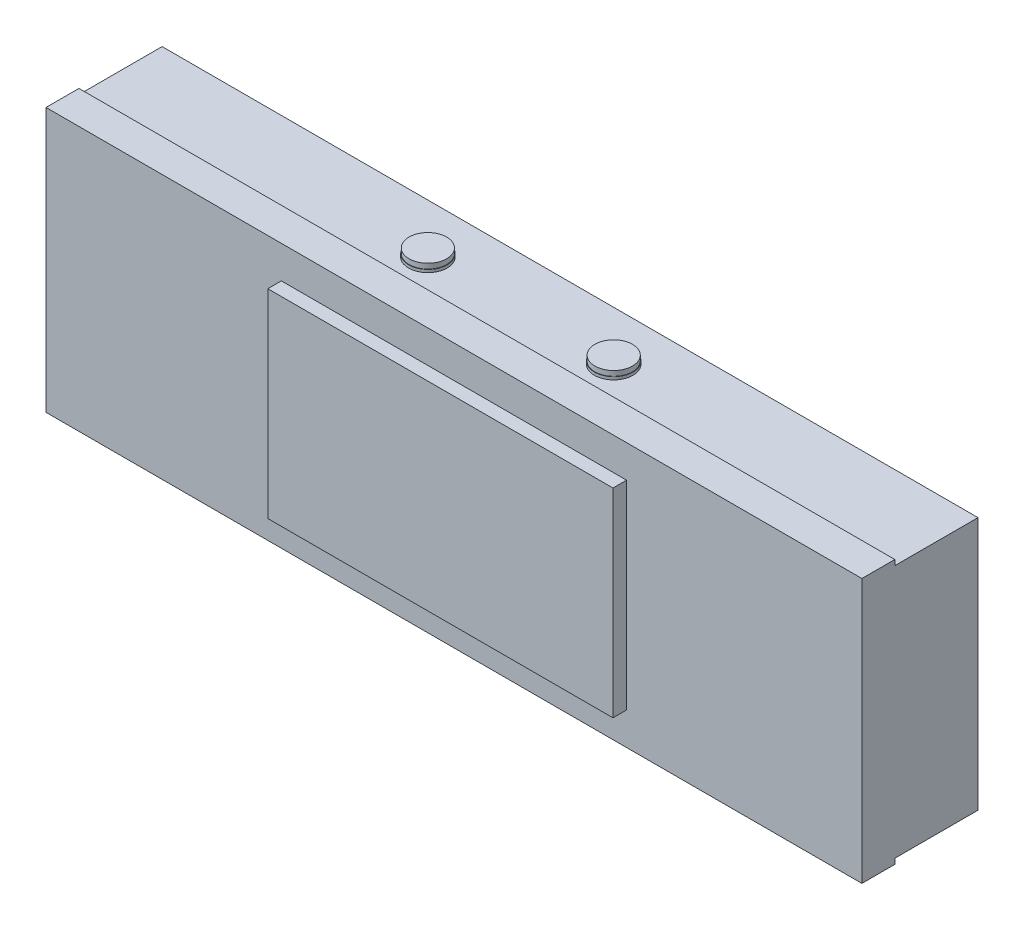
SolidWorks part; units mm, degrees
ref_plane "Front Plane" through (0, 0, 0) normal (0, 0, 1) x (1, 0, 0)
ref_plane "Top Plane" through (0, 0, 0) normal (0, 1, 0) x (1, 0, 0)
ref_plane "Right Plane" through (0, 0, 0) normal (1, 0, 0) x (0, 0, -1)
sketch "Sketch2" plane through (0, 0, 0) normal (1, 0, 0) x (0, 0, -1)
  line L0 (37, -40.375) -> (37, 40.375)
  line L1 (37, 40.375) -> (10.5, 40.375)
  line L2 (10.5, 40.375) -> (10.5, -40.375)
  line L3 (10.5, -40.375) -> (37, -40.375)
sketch "lid sketch" plane through (0, 0, 0) normal (1, 0, 0) x (0, 0, -1)
  line L0 (10.5, -42.075) -> (10.5, 42.075)
  line L1 (10.5, 42.075) -> (0, 42.075)
  line L2 (0, 42.075) -> (0, -42.075)
  line L3 (0, -42.075) -> (10.5, -42.075)
extrude "lid" add sketch "lid sketch" along normal mid plane 260
sketch "channel wall sketch" plane through (0, 0, 0) normal (1, 0, 0) x (0, 0, -1)
  line L0 (37, -40.375) -> (37, 40.375)
  line L1 (37, 40.375) -> (10.5, 40.375)
  line L2 (10.5, 40.375) -> (10.5, -40.375)
  line L3 (10.5, -40.375) -> (37, -40.375)
extrude "channel wall" add sketch "channel wall sketch" along normal mid plane 260
ref_plane "PZ 2.160" through (0, 0, 2.16) normal (0, 0, 1) x (1, 0, 0)
sketch "hanger plate and hardware sketch" plane through (0, 0, 2.16) normal (0, 0, 1) x (1, 0, 0)
  line L0 (-55, -31.715) -> (55, -31.715)
  line L1 (55, -31.715) -> (55, 31.715)
  line L2 (55, 31.715) -> (-55, 31.715)
  line L3 (-55, 31.715) -> (-55, -31.715)
extrude "hanger plate and hardware" add sketch "hanger plate and hardware sketch" along normal mid plane 4.32
ref_plane "PY 40.320" through (0, 40.32, 0) normal (0, 1, 0) x (1, 0, 0)
sketch "insert flanges +y sketch" plane through (0, 40.32, 0) normal (0, 1, 0) x (1, 0, 0)
  circle A0 centre (29.605, 21.3) radius 6.15
  circle A1 centre (-29.605, 21.3) radius 6.15
extrude "insert flanges +y" add sketch "insert flanges +y sketch" along normal mid plane 1.89
ref_plane "PY -40.320" through (0, -40.32, 0) normal (0, 1, 0) x (1, 0, 0)
sketch "insert flanges -y sketch" plane through (0, -40.32, 0) normal (0, 1, 0) x (1, 0, 0)
  circle A0 centre (29.605, 21.3) radius 6.15
  circle A1 centre (-29.605, 21.3) radius 6.15
extrude "insert flanges -y" add sketch "insert flanges -y sketch" along normal mid plane 1.89
ref_plane "PY 42.065" through (0, 42.065, 0) normal (0, 1, 0) x (1, 0, 0)
sketch "spacer washers +y sketch" plane through (0, 42.065, 0) normal (0, 1, 0) x (1, 0, 0)
  circle A0 centre (29.605, 21.3) radius 6
  circle A1 centre (-29.605, 21.3) radius 6
extrude "spacer washers +y" add sketch "spacer washers +y sketch" along normal mid plane 1.6
ref_plane "PY -42.065" through (0, -42.065, 0) normal (0, 1, 0) x (1, 0, 0)
sketch "spacer washers -y sketch" plane through (0, -42.065, 0) normal (0, 1, 0) x (1, 0, 0)
  circle A0 centre (29.605, 21.3) radius 6
  circle A1 centre (-29.605, 21.3) radius 6
extrude "spacer washers -y" add sketch "spacer washers -y sketch" along normal mid plane 1.6
equation "\"diffL\"= 608.8mm"
equation "\"diffW\"= 329.4mm"
equation "\"diffT\"= 2.9mm"
equation "\"chanSlotW\"= 12.9mm"
equation "\"chanSlotDepth\"= 11.13mm"
equation "\"chanFloor\"= 1.57mm"
equation "\"chanLeg\"= 12.7mm"
equation "\"lightL\"= 604.8mm"
equation "\"lightW\"= 330.2mm"
equation "\"lightH\"= 92mm"
equation "\"lightSideFlat\"= 30mm"
equation "\"lightSlopeLen\"= 38.9mm"
equation "\"lightWingDepth\"= 50.1mm"
equation "\"lightWingFlat\"= 90.2mm"
equation "\"lightChanW\"= 99.6mm"
equation "\"lightChanStand\"= 44.1mm"
equation "\"insFlangeD\"= 12.3mm"
equation "\"insFromEnd\"= 20.7mm"
equation "\"insUpSlope\"= 20.8mm"
equation "\"gaugeH\"= 10mm"
equation "\"gaugeStepLen\"= 14mm"
equation "\"gaugeStepW0\"= 13.1mm"
equation "\"gaugeStepDW\"= 0.2mm"
equation "\"gaugeSteps\"= 5mm"
equation "\"gaugeHandleLen\"= 30mm"
equation "\"gaugeHandleW\"= 24mm"
equation "\"gaugeSlot0\"= 3mm"
equation "\"gaugeSlotD\"= 0.1mm"
equation "\"gaugeSlotDepth\"= 8mm"
equation "\"gap\"= 25.4mm"
equation "\"edgeL\"= 1mm"
equation "\"edgeW\"= 0.75mm"
equation "\"proud\"= 2.5mm"
equation "\"seatClr\"= 0.15mm"
equation "\"tongueClrZ\"= 0.1mm"
equation "\"tongueClrX\"= 0.25mm"
equation "\"tongueLen\"= 30mm"
equation "\"armSide\"= 45mm"
equation "\"armEnd\"= 20mm"
equation "\"brkW\"= 26mm"
equation "\"brkT\"= 7mm"
equation "\"brkSeatClr\"= 0.3mm"
equation "\"brkScrewSpan\"= 16mm"
equation "\"pilotD\"= 4.3mm"
equation "\"pilotDepth\"= 8mm"
equation "\"screwClrD\"= 3.8mm"
equation "\"jogBelow\"= 4mm"
equation "\"padT\"= 7mm"
equation "\"padLen\"= 36mm"
equation "\"m6Clr\"= 9mm"
equation "\"m6Slot\"= 5mm"
equation "\"flangeRelD\"= 18mm"
equation "\"flangeRelDepth\"= 1.5mm"
equation "\"relLen\"= 5mm"
equation "\"relDepth\"= 3.3mm"
equation "\"knockN\"= 100mm"
equation "\"petgcfE\"= 3000mm"
equation "\"mockExtent\"= 110mm"
equation "\"relZnear\"= 9.4mm"
equation "\"relZfar\"= 23.4mm"
equation "\"headD\"= 8mm"
equation "\"headH\"= 2.5mm"
equation "\"headFromEnd\"= 6.8mm"
equation "\"headBack\"= 16.4mm"
equation "\"sideClr\"= 0.4mm"
equation "\"cornerRelR\"= 1.5mm"
equation "\"cornerRelBack\"= 0.6mm"
equation "\"endHeadH\"= 2.8mm"
equation "\"footClr\"= 1.2mm"
equation "\"footEndClr\"= 3.5mm"
equation "\"footBlockClr\"= 0.5mm"
equation "\"footBack\"= 85mm"
equation "\"footFwd\"= 10mm"
equation "\"footBraceEnd\"= 3mm"
equation "\"spacerLen\"= 60mm"
equation "\"spacerShort\"= 0.5mm"
equation "\"spacerCham\"= 0.8mm"
equation "\"spacerPerSide\"= 3mm"
equation "\"spacerPerEnd\"= 1mm"
equation "\"toolR\"= 9mm"
equation "\"visR\"= 4mm"
equation "\"edgeR\"= 1mm"
equation "\"bendOutR\"= 5mm"
equation "\"insideR\"= 2.5mm"
equation "\"footCornerR\"= 10mm"
equation "\"footFrontR\"= 8mm"
equation "\"braceKinkR\"= 12mm"
equation "\"bedCham\"= 1mm"
equation "\"bedChamSmall\"= 0.6mm"
equation "\"soleTopR\"= 2mm"
equation "\"cornerR\"= 6mm"
equation "\"rimInR\"= 1mm"
equation "\"insFlangeH\"= 1mm"
equation "\"insHoleFinishD\"= 4.5mm"
equation "\"insLen\"= 6.4mm"
equation "\"cgInset\"= 4mm"
equation "\"lampWeightN\"= 51mm"
equation "\"frameWeightN\"= 10mm"
equation "\"bumpIn\"= 8mm"
equation "\"bumpH\"= 3mm"
equation "\"legBelowFront\"= 2mm"
equation "\"lipClr\"= 0.1mm"
equation "\"revealR\"= 2mm"
equation "\"frontCham\"= 1mm"
equation "\"leanDeg\"= 5mm"
equation "\"footTailT\"= 6mm"
equation "\"v1LeanDeg\"= 4.5mm"
equation "\"toeNoseR\"= 5mm"
equation "\"petgE\"= 2000mm"
equation "\"cheekT\"= 8mm"
equation "\"handleUp\"= 50mm"
equation "\"handleZ\"= -10mm"
equation "\"gripD\"= 19.05mm"
equation "\"gripClr\"= 0.5mm"
equation "\"bossWall\"= 5mm"
equation "\"bossLen\"= 14mm"
equation "\"socketFloor\"= 4mm"
equation "\"barEndClr\"= 1mm"
equation "\"lipH\"= 4mm"
equation "\"lipDeep\"= 6mm"
equation "\"stripT\"= 1.3mm"
equation "\"stripW\"= 12mm"
equation "\"stripClr\"= 0.5mm"
equation "\"stripBack\"= 3mm"
equation "\"endRelClr\"= 1mm"
equation "\"cornerScrewX\"= 5.5mm"
equation "\"cornerScrewZ\"= 6mm"
equation "\"cornerScrewD\"= 8.5mm"
equation "\"footTabIn\"= 33mm"
equation "\"footTabZ1\"= 50mm"
equation "\"footTabZ2\"= 19mm"
equation "\"footTabR\"= 8mm"
equation "\"landAx0\"= -17mm"
equation "\"landAz0\"= -30mm"
equation "\"landAx1\"= -3mm"
equation "\"landAz1\"= -18mm"
equation "\"landBx0\"= -60mm"
equation "\"landBz0\"= -43mm"
equation "\"landBx1\"= -46mm"
equation "\"landBz1\"= -27mm"
equation "\"sdLidW\"= 84.15mm"
equation "\"sdChanW\"= 80.19mm"
equation "\"sdLidStep\"= 1.7mm"
equation "\"sdInsRecess\"= 0.81mm"
equation "\"sdInsSpan\"= 59.21mm"
equation "\"sdJunkIn\"= 10.36mm"
equation "\"sdJunkH\"= 4.32mm"
equation "\"sdJunkLen\"= 110mm"
equation "\"sdInsDown\"= 22mm"
equation "\"sdSkirtH\"= 10.5mm"
equation "\"sdWallDown\"= 37mm"
equation "\"sdLidClr\"= 0.8mm"
equation "\"sdWasherT\"= 1.6mm"
equation "\"sdWasherD\"= 12mm"
equation "\"sdLegT\"= 5mm"
equation "\"sdLegBelow\"= 11mm"
equation "\"sdLegHalf\"= 46mm"
equation "\"sdSkirtSlope\"= 50mm"
equation "\"sdLipH\"= 5mm"
equation "\"sdLeadCham\"= 1mm"
equation "\"sdJunkSide\"= 1.5mm"
equation "\"sdRecessH\"= 6mm"
equation "\"sdRoofT\"= 6mm"
equation "\"sdOpenL\"= 114.3mm"
equation "\"sdOpenH\"= 50.8mm"
equation "\"sdGripD\"= 25mm"
equation "\"sdBendR\"= 18mm"
equation "\"sdBaseR\"= 8mm"
equation "\"sdEndMargin\"= 2mm"
equation "\"sdSlotW\"= 7mm"
equation "\"sdSlotFloat\"= 2mm"
equation "\"sdEdgeR\"= 2mm"
